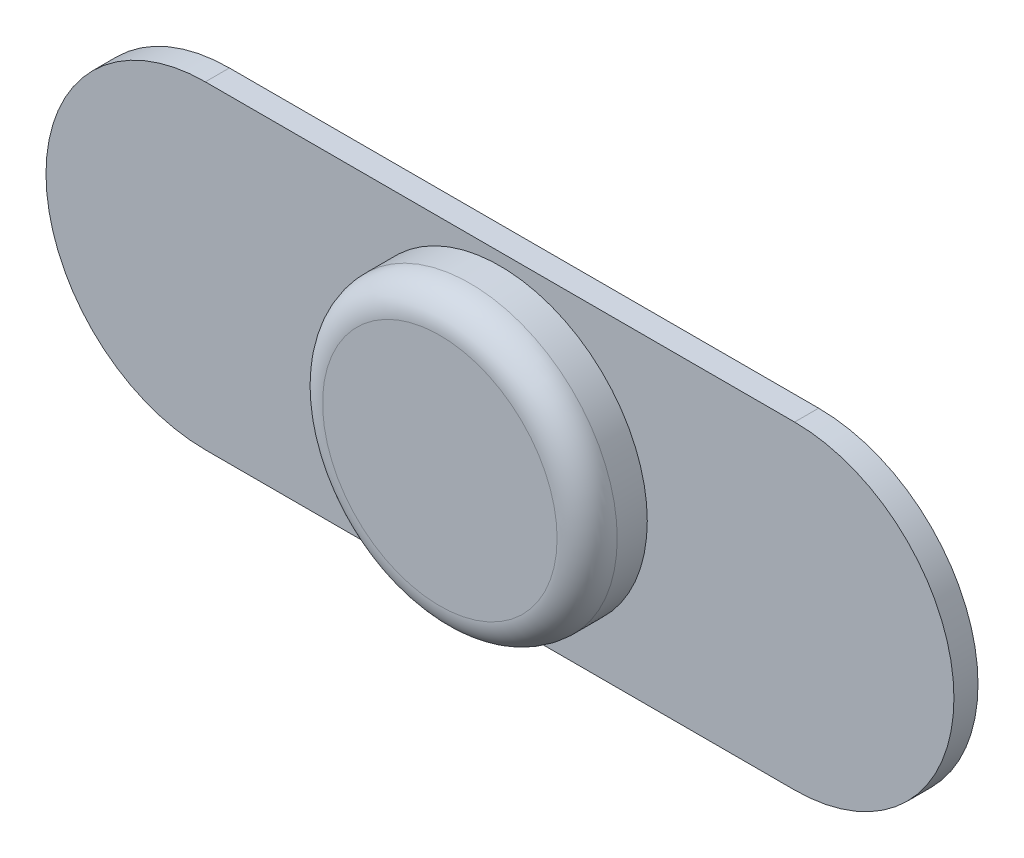
SolidWorks part; units mm, degrees
ref_plane "Ebene vorne" through (0, 0, 0) normal (0, 0, 1) x (1, 0, 0)
ref_plane "Ebene oben" through (0, 0, 0) normal (0, 1, 0) x (1, 0, 0)
ref_plane "Ebene rechts" through (0, 0, 0) normal (1, 0, 0) x (0, 0, -1)
sketch "Skizze1" plane through (0, 0, 0) normal (0, 0, 1) x (1, 0, 0)
  circle A0 centre (0, 0) radius 2.45
  dimension "D1" = 4.9
extrude "Aufsatz-Linear austragen1" add sketch "Skizze1" along normal blind 1
sketch "Skizze2" plane through (0, 0, 0) normal (0, 0, -1) x (-1, 0, 0)
  line L0 (-4.9, 0) -> (4.9, 0) construction
  line L1 (-4.9, 2.65) -> (4.9, 2.65)
  line L2 (-4.9, -2.65) -> (4.9, -2.65)
  arc A0 (-4.9, 2.65) -> (-4.9, -2.65) centre (-4.9, 0) ccw
  arc A1 (4.9, -2.65) -> (4.9, 2.65) centre (4.9, 0) ccw
  point P2 (0, 0)
  dimension "D1" = 9.8
  dimension "D2" = 5.3
extrude "Aufsatz-Linear austragen2" add sketch "Skizze2" along normal blind 0.4
fillet "Verrundung1" radius 0.5 1 edges at (2.45, 0, 1)
sketch "Skizze3" plane through (0, 0, -0.4) normal (0, 0, -1) x (-1, 0, 0)
  circle A0 centre (0, 0) radius 1.25
  dimension "D1" = 2.5
extrude "Schnitt-Linear austragen1" [suppressed] cut sketch "Skizze3" against normal blind 0.35
